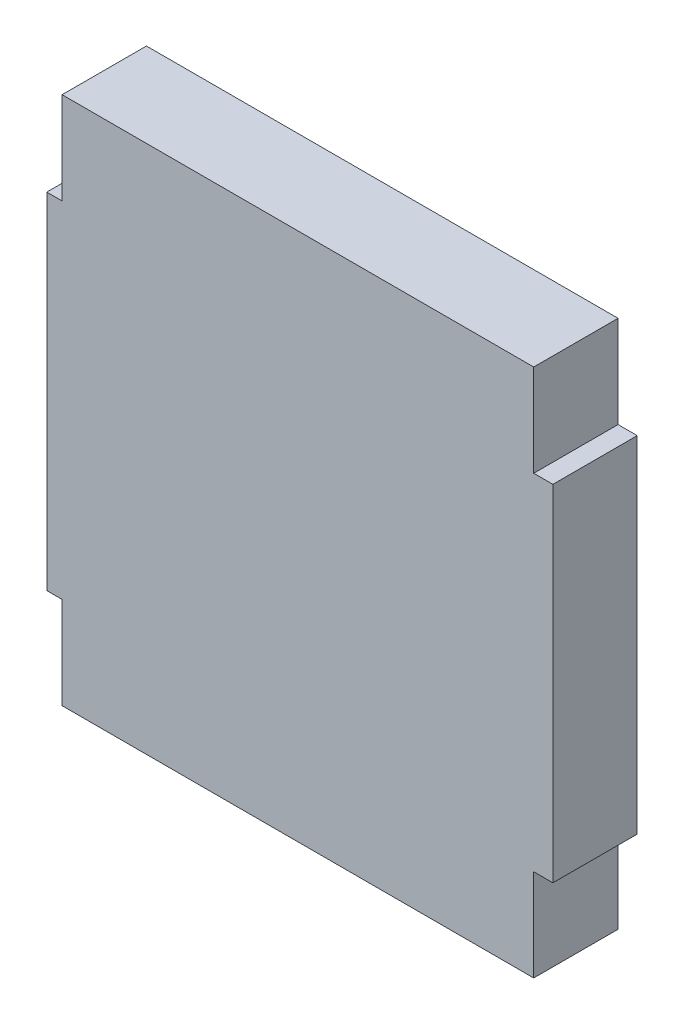
SolidWorks part; units mm, degrees
ref_plane "前视基准面" through (0, 0, 0) normal (0, 0, 1) x (1, 0, 0)
ref_plane "上视基准面" through (0, 0, 0) normal (0, 1, 0) x (1, 0, 0)
ref_plane "右视基准面" through (0, 0, 0) normal (1, 0, 0) x (0, 0, -1)
sketch "草图1" plane through (0, 0, 0) normal (0, 0, 1) x (1, 0, 0)
  line L0 (-3.275, -2.25) -> (-3.075, -2.25)
  line L1 (-3.075, -2.25) -> (-3.075, -3.45)
  line L2 (-3.075, -3.45) -> (3.075, -3.45)
  line L3 (3.075, -3.45) -> (3.075, -2.25)
  line L4 (3.075, -2.25) -> (3.325, -2.25)
  line L5 (3.325, -2.25) -> (3.325, 2.25)
  line L6 (3.325, 2.25) -> (3.075, 2.25)
  line L7 (3.075, 2.25) -> (3.075, 3.45)
  line L8 (3.075, 3.45) -> (-3.075, 3.45)
  line L9 (-3.075, 3.45) -> (-3.075, 2.25)
  line L10 (-3.075, 2.25) -> (-3.2, 2.25)
  line L11 (-3.2, 2.25) -> (-3.275, 2.25)
  line L12 (-3.275, 2.25) -> (-3.275, -2.25)
extrude "Component_Outline" add sketch "草图1" along normal blind 1.1 separate body
sketch3d "3D草图1"
  line L0 (0, 0, 0) -> (1, 0, 0)
  line L1 (0, 0, 0) -> (0, 1, 0)
  line L2 (0, 0, 0) -> (0, 0, 1)
  point P0 (0, 0, 0)
